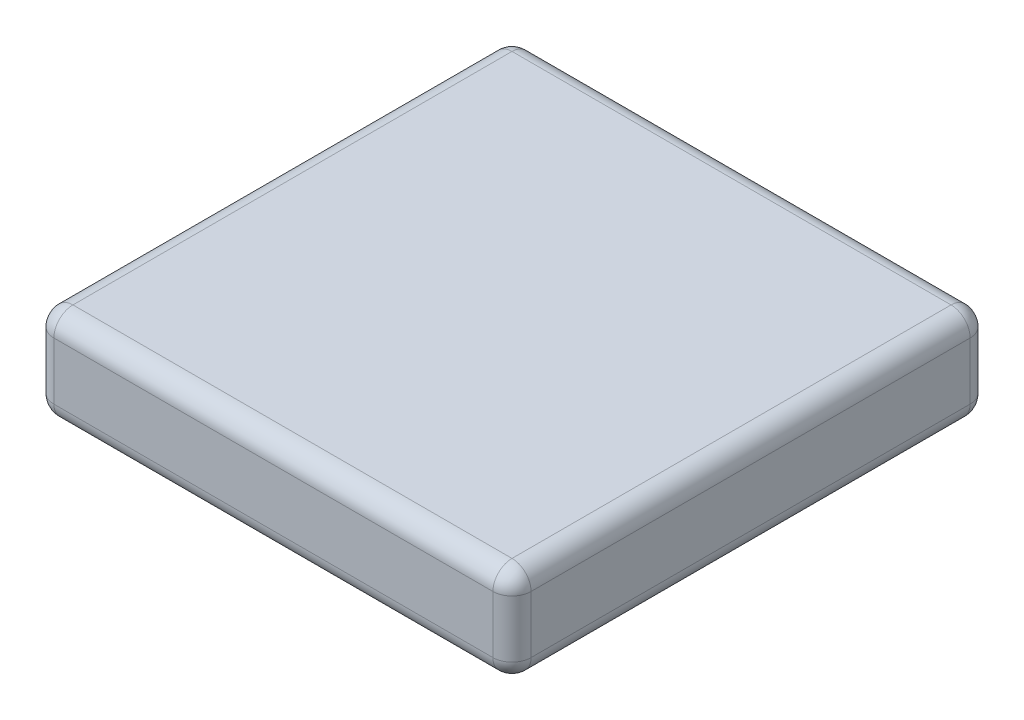
SolidWorks part; units mm, degrees
ref_plane "Front Plane" through (0, 0, 0) normal (0, 0, 1) x (1, 0, 0)
ref_plane "Top Plane" through (0, 0, 0) normal (0, 1, 0) x (1, 0, 0)
ref_plane "Right Plane" through (0, 0, 0) normal (1, 0, 0) x (0, 0, -1)
sketch "Sketch1" plane through (0, 0, 0) normal (0, 1, 0) x (1, 0, 0)
  line L1 (25, -25) -> (-25, -25)
  line L2 (25, -25) -> (25, 25)
  line L3 (25, 25) -> (-25, 25)
  line L4 (-25, -25) -> (-25, 25)
  line L5 (25, -25) -> (-25, 25) construction
  line L6 (25, 25) -> (-25, -25) construction
  point P0 (0, 0)
  dimension "D1" = 50
  dimension "D2" = 50
extrude "Boss-Extrude1" add sketch "Sketch1" along normal blind 10
fillet "Fillet1" radius 2 1 edges at (0, 10, 25)
fillet "Fillet2" radius 2 3 edges at (25, 4, 25) (25, 9.4142, 24.4142) (25, 10, -1)
fillet "Fillet3" radius 2 3 edges at (25, 4, -25) (24.4142, 9.4142, -25) (-1, 10, -25)
fillet "Fillet4" radius 2 5 edges at (-25, 4, -25) (-25, 9.4142, -24.4142) (-25, 4, 25) (-25, 9.4142, 24.4142) (-25, 10, 0)
fillet "Fillet5" radius 2 8 edges at (-24.4142, 0, -24.4142) (0, 0, -25) (24.4142, 0, -24.4142) (25, 0, 0) (24.4142, 0, 24.4142) (0, 0, 25) (-24.4142, 0, 24.4142) (-25, 0, 0)
